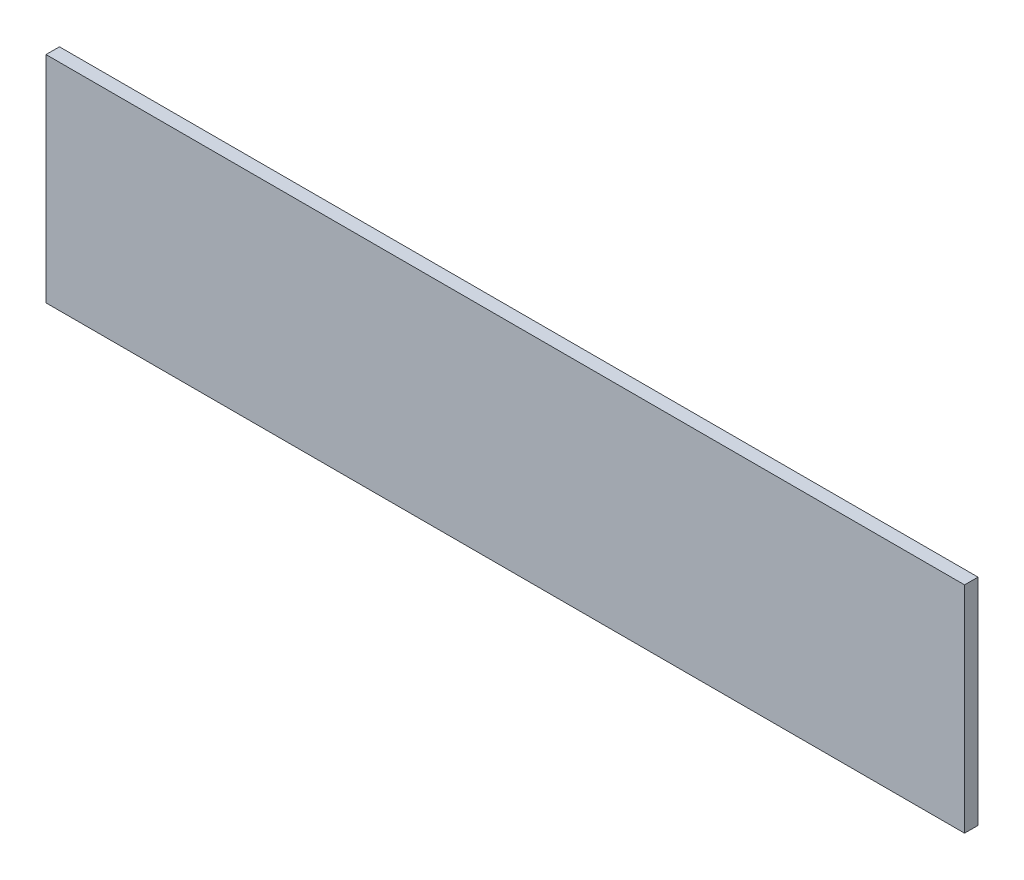
SolidWorks part; units mm, degrees
material "ASTM A36 Steel"
ref_plane "Front Plane" through (0, 0, 0) normal (0, 0, 1) x (1, 0, 0)
ref_plane "Top Plane" through (0, 0, 0) normal (0, 1, 0) x (1, 0, 0)
ref_plane "Right Plane" through (0, 0, 0) normal (1, 0, 0) x (0, 0, -1)
sketch "Sketch1" plane through (0, 0, 0) normal (0, 0, 1) x (1, 0, 0)
  line L1 (-102.5, 24) -> (102.5, 24)
  line L2 (-102.5, 24) -> (-102.5, -24)
  line L3 (-102.5, -24) -> (102.5, -24)
  line L4 (102.5, 24) -> (102.5, -24)
  line L5 (-102.5, 24) -> (102.5, -24) construction
  line L6 (-102.5, -24) -> (102.5, 24) construction
  point P0 (0, 0)
  dimension "D1" = 48
  dimension "D2" = 205
extrude "Boss-Extrude1" add sketch "Sketch1" along normal blind 3
